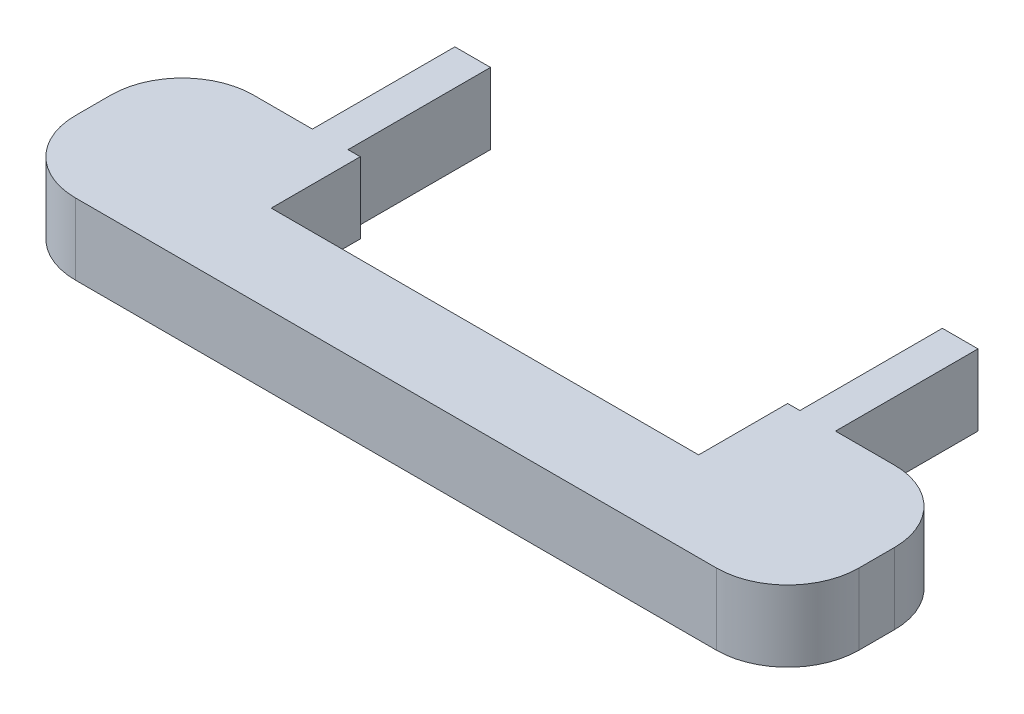
SolidWorks part; units mm, degrees
ref_plane "Front Plane" through (0, 0, 0) normal (0, 0, 1) x (1, 0, 0)
ref_plane "Top Plane" through (0, 0, 0) normal (0, 1, 0) x (1, 0, 0)
ref_plane "Right Plane" through (0, 0, 0) normal (1, 0, 0) x (0, 0, -1)
sketch "Sketch1" plane through (0, 0, 0) normal (0, 1, 0) x (1, 0, 0)
  line L1 (-27.94, -6.35) -> (27.94, -6.35)
  line L2 (-27.94, -6.35) -> (-27.94, 6.35)
  line L3 (-27.94, 6.35) -> (27.94, 6.35)
  line L4 (27.94, -6.35) -> (27.94, 6.35)
  line L5 (-27.94, -6.35) -> (27.94, 6.35) construction
  line L6 (-27.94, 6.35) -> (27.94, -6.35) construction
  point P0 (0, 0)
  dimension "D1" = 12.7
  dimension "D2" = 55.88
extrude "Boss-Extrude1" add sketch "Sketch1" along normal blind 5.08
sketch "Sketch2" plane through (0, 5.08, 0) normal (0, 1, 0) x (1, 0, 0)
  line L0 (0, 0) -> (0, 3.175) construction
  line L1 (27.94, 6.35) -> (-27.94, 6.35) construction
  line L2 (-15.24, 0) -> (15.24, 0)
  line L3 (-15.24, 0) -> (-15.24, 6.35)
  line L4 (-15.24, 6.35) -> (15.24, 6.35)
  line L5 (15.24, 0) -> (15.24, 6.35)
  line L6 (-15.24, 0) -> (15.24, 6.35) construction
  line L7 (-15.24, 6.35) -> (15.24, 0) construction
  dimension "D1" = 6.35
  dimension "D2" = 30.48
extrude "Cut-Extrude1" cut sketch "Sketch2" against normal blind 5.08
fillet "Fillet1" radius 5.08 4 edges at (-27.94, 2.54, 6.35) (-27.94, 2.54, -6.35) (27.94, 2.54, -6.35) (27.94, 2.54, 6.35)
sketch "Sketch3" plane through (0, 0, -6.35) normal (0, 0, -1) x (-1, 0, 0)
  line L0 (15.24, 0) -> (22.86, 0) construction
  line L1 (16.1125, 0) -> (18.6525, 0)
  line L2 (16.1125, 0) -> (16.1125, 5.08)
  line L3 (16.1125, 5.08) -> (18.6525, 5.08)
  line L4 (18.6525, 0) -> (18.6525, 5.08)
  line L5 (15.24, 5.08) -> (22.86, 5.08) construction
  dimension "D1" = 2.54
extrude "Boss-Extrude2" add sketch "Sketch3" along normal blind 10.16
mirror "Mirror1" about plane through (0, 0, 0) normal (1, 0, 0) of "Boss-Extrude2"
